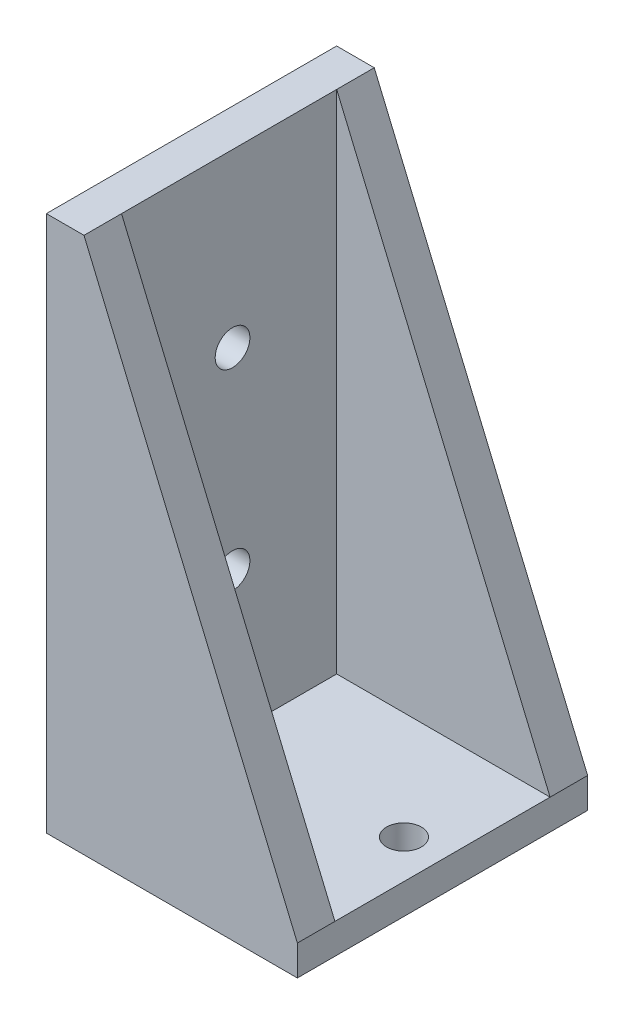
SolidWorks part; units mm, degrees
ref_plane "Front Plane" through (0, 0, 0) normal (0, 0, 1) x (1, 0, 0)
ref_plane "Top Plane" through (0, 0, 0) normal (0, 1, 0) x (1, 0, 0)
ref_plane "Right Plane" through (0, 0, 0) normal (1, 0, 0) x (0, 0, -1)
sketch "Sketch1" plane through (0, 0, 0) normal (0, 0, 1) x (1, 0, 0)
  line L0 (1.8433, 26.29) -> (12.3, 1.4827)
  line L1 (0, 0) -> (12.3, 0)
  line L2 (0, 0) -> (0, 26.29)
  line L3 (0, 26.29) -> (1.8433, 26.29)
  line L4 (12.3, 0) -> (12.3, 1.4827)
  dimension "D1" = 12.3
  dimension "D2" = 26.29
extrude "Boss-Extrude1" add sketch "Sketch1" along normal blind 14.224
sketch "Sketch2" plane through (0, 26.29, 0) normal (0, 1, 0) x (1, 0, 0)
  line L0 (1.8433, -14.224) -> (1.8433, 0) construction
  line L1 (1.8433, -1.84) -> (12.3, -1.84)
  line L2 (1.8433, -1.84) -> (1.8433, -12.384)
  line L3 (1.8433, -12.384) -> (12.3, -12.384)
  line L4 (12.3, -1.84) -> (12.3, -12.384)
  line L5 (1.8433, 0) -> (0, 0) construction
  line L7 (1.8433, 0) -> (1.8433, -1.84) construction
  line L8 (1.8433, -12.384) -> (1.8433, -14.224) construction
  line L9 (12.3, -14.224) -> (12.3, 0) construction
  dimension "D1" = 1.84
  dimension "D2" = 0
extrude "Cut-Extrude1" cut sketch "Sketch2" against normal up to vertex (24.8073 mm away)
sketch "Sketch3" plane through (0, 0, 0) normal (-1, 0, 0) x (0, 0, 1)
  line L0 (7.9629, 0) -> (6.2611, 0) construction
  line L1 (7.9629, 0) -> (6.2611, 0) construction
  line L2 (7.9629, 0) -> (6.2611, 0)
  line L3 (7.9629, 0) -> (6.2611, 0)
  circle A0 centre (6.944, 17.8835) radius 0.8509 construction
  circle A1 centre (6.944, 8.4171) radius 0.8509 construction
  circle A2 centre (6.944, 17.8835) radius 0.8509
  circle A3 centre (6.944, 8.4171) radius 0.8509
extrude "Cut-Extrude2" cut sketch "Sketch3" against normal blind 10 contours A2 | A3
sketch "Sketch4" plane through (0, 0, 0) normal (0, -1, 0) x (1, 0, 0)
  circle A0 centre (10.4099, 7.112) radius 0.8509 construction
  circle A1 centre (0.9436, 7.112) radius 0.8509 construction
  circle A2 centre (10.4099, 7.112) radius 0.8509
  circle A3 centre (0.9436, 7.112) radius 0.8509
extrude "Cut-Extrude3" cut sketch "Sketch4" against normal up to surface (1.4827 mm away) up to face at (7.0717, 1.4827, 7.112)
